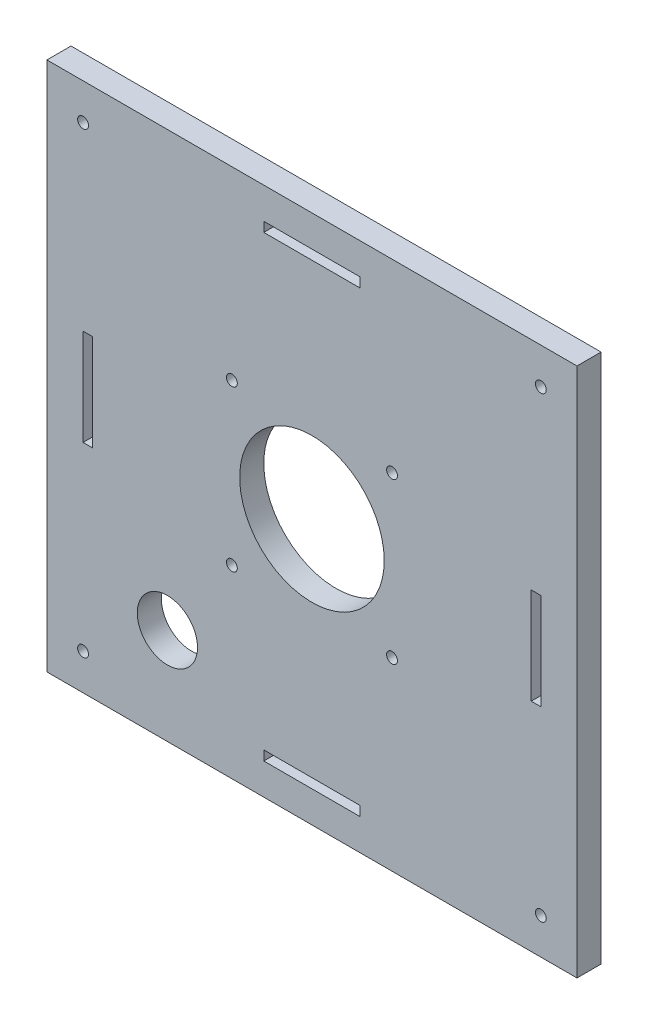
SolidWorks part; units mm, degrees
material "Aleación 6061"
ref_plane "Alzado" through (0, 0, 0) normal (0, 0, 1) x (1, 0, 0)
ref_plane "Planta" through (0, 0, 0) normal (0, 1, 0) x (1, 0, 0)
ref_plane "Vista lateral" through (0, 0, 0) normal (1, 0, 0) x (0, 0, -1)
sketch "Sk_Placa" plane through (0, 0, 0) normal (0, 0, 1) x (1, 0, 0)
  line L1 (-110, -110) -> (110, -110)
  line L2 (-110, -110) -> (-110, 110)
  line L3 (-110, 110) -> (110, 110)
  line L4 (110, -110) -> (110, 110)
  line L5 (-110, -110) -> (110, 110) construction
  line L6 (-110, 110) -> (110, -110) construction
  point P0 (0, 0)
  dimension "D1" = 220
  dimension "D2" = 220
extrude "Placa" add sketch "Sk_Placa" along normal blind 10
sketch "Sk_Paso_cables" plane through (0, 0, 0) normal (0, 0, 1) x (1, 0, 0)
  circle A0 centre (0, 0) radius 30
  dimension "D1" = 60
extrude "Paso_cables" cut sketch "Sk_Paso_cables" along normal blind 10
sketch "Sk_Pasantes_M4_pedestal" plane through (0, 0, 0) normal (0, 0, 1) x (1, 0, 0)
  circle A0 centre (33.234, 33.234) radius 2.25
  circle A1 centre (-33.234, 33.234) radius 2.25
  circle A2 centre (-33.234, -33.234) radius 2.25
  circle A3 centre (33.234, -33.234) radius 2.25
  dimension "D1" = 4.5
  dimension "D4" = 4.5
  dimension "D7" = 4.5
  dimension "D10" = 4.5
  dimension "D2" = 33.234
  dimension "D3" = 33.234
  dimension "D5" = 33.234
  dimension "D6" = 33.234
  dimension "D8" = 33.234
  dimension "D9" = 33.234
  dimension "D11" = 33.234
  dimension "D12" = 33.234
extrude "Pasantes_M4_pedestal" cut sketch "Sk_Pasantes_M4_pedestal" along normal blind 10
sketch "Sk_Cajas_M4_inferiores" plane through (0, 0, 0) normal (0, 0, 1) x (1, 0, 0)
  circle A0 centre (33.234, 33.234) radius 4
  circle A1 centre (-33.234, 33.234) radius 4
  circle A2 centre (-33.234, -33.234) radius 4
  circle A3 centre (33.234, -33.234) radius 4
  dimension "D1" = 8
  dimension "D4" = 8
  dimension "D7" = 8
  dimension "D10" = 8
  dimension "D2" = 33.234
  dimension "D3" = 33.234
  dimension "D5" = 33.234
  dimension "D6" = 33.234
  dimension "D8" = 33.234
  dimension "D9" = 33.234
  dimension "D11" = 33.234
  dimension "D12" = 33.234
extrude "Cajas_M4_inferiores" cut sketch "Sk_Cajas_M4_inferiores" along normal blind 4.5
sketch "Sk_Pasantes_M4_separadores_caja" plane through (0, 0, 0) normal (0, 0, 1) x (1, 0, 0)
  circle A0 centre (-95, -95) radius 2.25
  circle A1 centre (-95, 95) radius 2.25
  circle A2 centre (95, -95) radius 2.25
  circle A3 centre (95, 95) radius 2.25
  dimension "D1" = 4.5
  dimension "D4" = 4.5
  dimension "D7" = 4.5
  dimension "D10" = 4.5
  dimension "D2" = 95
  dimension "D3" = 95
  dimension "D5" = 95
  dimension "D6" = 95
  dimension "D8" = 95
  dimension "D9" = 95
  dimension "D11" = 95
  dimension "D12" = 95
extrude "Pasantes_M4_separadores_caja" cut sketch "Sk_Pasantes_M4_separadores_caja" along normal blind 10
sketch "Sk_Paso_cables_caja" plane through (0, 0, 0) normal (0, 0, 1) x (1, 0, 0)
  circle A0 centre (-60, -70) radius 12.5
  dimension "D1" = 25
  dimension "D2" = 60
  dimension "D3" = 70
extrude "Paso_cables_caja" cut sketch "Sk_Paso_cables_caja" along normal blind 10
sketch "Croquis1" plane through (0, 0, 10) normal (0, 0, 1) x (1, 0, 0)
  line L0 (-91.5, -95) -> (91.5, -95) construction
  line L1 (-110, -110) -> (110, -110) construction
  line L2 (-20, -97) -> (20, -97)
  line L3 (-20, -97) -> (-20, -93)
  line L4 (-20, -93) -> (20, -93)
  line L5 (20, -97) -> (20, -93)
  line L6 (-20, -97) -> (20, -93) construction
  line L7 (-20, -93) -> (20, -97) construction
  line L8 (-110, 0) -> (110, 0) construction
  line L9 (-110, 110) -> (-110, -110) construction
  line L10 (110, -110) -> (110, 110) construction
  line L11 (0, -110) -> (0, 110) construction
  line L12 (110, 110) -> (-110, 110) construction
  line L13 (20, 97) -> (20, 93)
  line L14 (-20, 93) -> (20, 93)
  line L15 (-20, 97) -> (20, 97)
  line L16 (-20, 97) -> (-20, 93)
  line L17 (95, -20) -> (91, -20)
  line L22 (95, 20) -> (91, 20)
  line L23 (95, 20) -> (95, -20)
  line L24 (-95, 20) -> (-91, 20)
  line L25 (-95, 20) -> (-95, -20)
  line L26 (-95, -20) -> (-91, -20)
  line L27 (-91, 20) -> (-91, -20)
  line L28 (-95, 20) -> (-91, -20) construction
  line L29 (-95, -20) -> (-91, 20) construction
  line L30 (91, 20) -> (91, -20)
  point P2 (0, -95)
  point P3 (0, -95)
  point P30 (-93, 0)
  dimension "D1" = 183
  dimension "D2" = 4
  dimension "D3" = 40
  dimension "D4" = 15
  dimension "D5" = 4
  dimension "D6" = 40
  dimension "D7" = 15
extrude "Cortar-Extruir1" cut sketch "Croquis1" against normal through all
